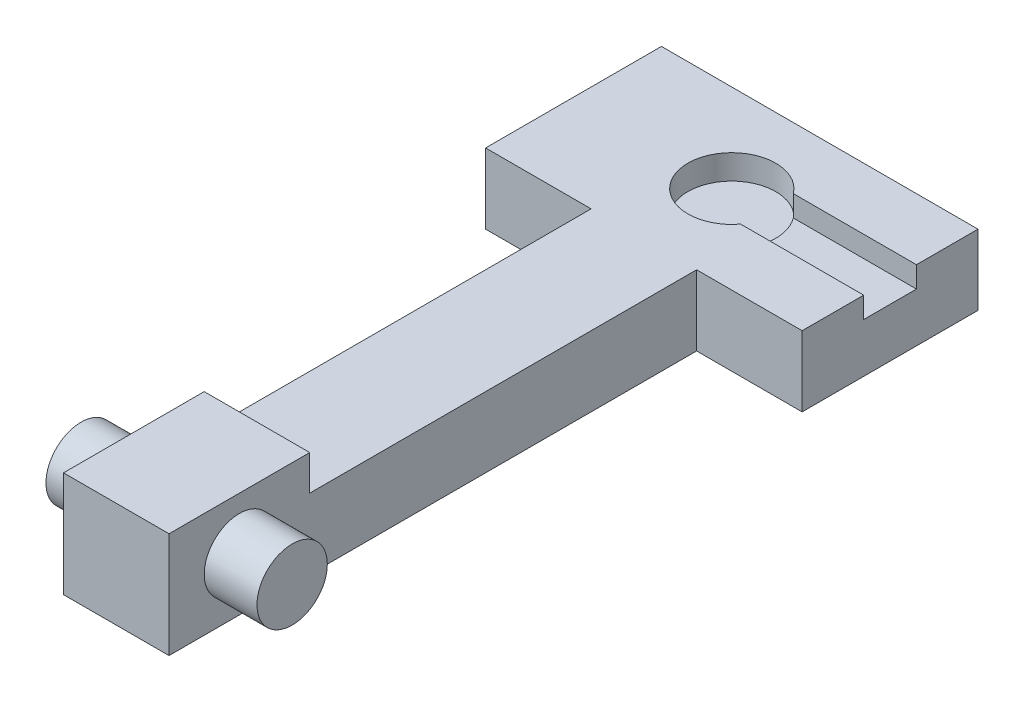
SolidWorks part; units mm, degrees
ref_plane "Front Plane" through (0, 0, 0) normal (0, 0, 1) x (1, 0, 0)
ref_plane "Top Plane" through (0, 0, 0) normal (0, 1, 0) x (1, 0, 0)
ref_plane "Right Plane" through (0, 0, 0) normal (1, 0, 0) x (0, 0, -1)
sketch "Sketch1" plane through (0, 0, 0) normal (0, 1, 0) x (1, 0, 0)
  line L0 (0, 0) -> (30, 0)
  line L1 (30, 0) -> (30, 150)
  line L2 (0, 0) -> (0, 150)
  line L4 (0, 150) -> (-30, 150)
  line L5 (-30, 150) -> (-30, 200)
  line L6 (-30, 200) -> (60, 200)
  line L7 (60, 200) -> (60, 150)
  line L8 (60, 150) -> (30, 150)
  dimension "D1" = 150
  dimension "D2" = 30
  dimension "D3" = 30
  dimension "D4" = 50
extrude "Boss-Extrude1" add sketch "Sketch1" along normal blind 20
sketch "Sketch2" plane through (0, 20, 0) normal (0, 1, 0) x (1, 0, 0)
  line L1 (0, 0) -> (30, 0) construction
  line L2 (15, 0) -> (15, 200) construction
  line L3 (60, 200) -> (-30, 200) construction
  line L4 (60, 175) -> (-30, 175) construction
  line L5 (60, 150) -> (60, 200) construction
  line L6 (-30, 200) -> (-30, 150) construction
  circle A0 centre (15, 175) radius 12.5
  point P14 (15, 111.206)
  dimension "D1" = 25
extrude "Cut-Extrude1" cut sketch "Sketch2" against normal blind 7
sketch "Sketch3" plane through (0, 20, 0) normal (0, 1, 0) x (1, 0, 0)
  line L0 (60, 150) -> (60, 200) construction
  line L1 (60, 182.5) -> (22, 182.5)
  line L2 (60, 182.5) -> (60, 167.5)
  line L3 (60, 167.5) -> (22, 167.5)
  line L4 (22, 182.5) -> (22, 167.5)
  line L5 (30, 150) -> (60, 150) construction
  dimension "D1" = 17.5
  dimension "D2" = 15
  dimension "D3" = 38
extrude "Cut-Extrude2" cut sketch "Sketch3" against normal blind 6
sketch "Sketch7" plane through (0, 20, 0) normal (0, 1, 0) x (1, 0, 0)
  line L0 (0, 150) -> (0, 0) construction
  line L1 (30, 0) -> (0, 0)
  line L2 (30, 0) -> (30, 40)
  line L3 (30, 40) -> (0, 40)
  line L4 (0, 0) -> (0, 40)
  dimension "D1" = 40
extrude "Boss-Extrude2" add sketch "Sketch7" along normal blind 10
sketch "Sketch8" plane through (30, 0, 0) normal (1, 0, 0) x (0, 0, -1)
  line L0 (20, 30) -> (20, 0) construction
  line L1 (0, 30) -> (40, 30) construction
  line L2 (0, 0) -> (150, 0) construction
  line L3 (0, 15) -> (38.6017, 15) construction
  line L4 (0, 30) -> (0, 0) construction
  circle A0 centre (20, 15) radius 10
  point P12 (0, 0)
  point P13 (0, 0)
  point P14 (20, 12.8134)
  dimension "D1" = 20
extrude "Boss-Extrude3" add sketch "Sketch8" along normal blind 15 and the other way blind 45
